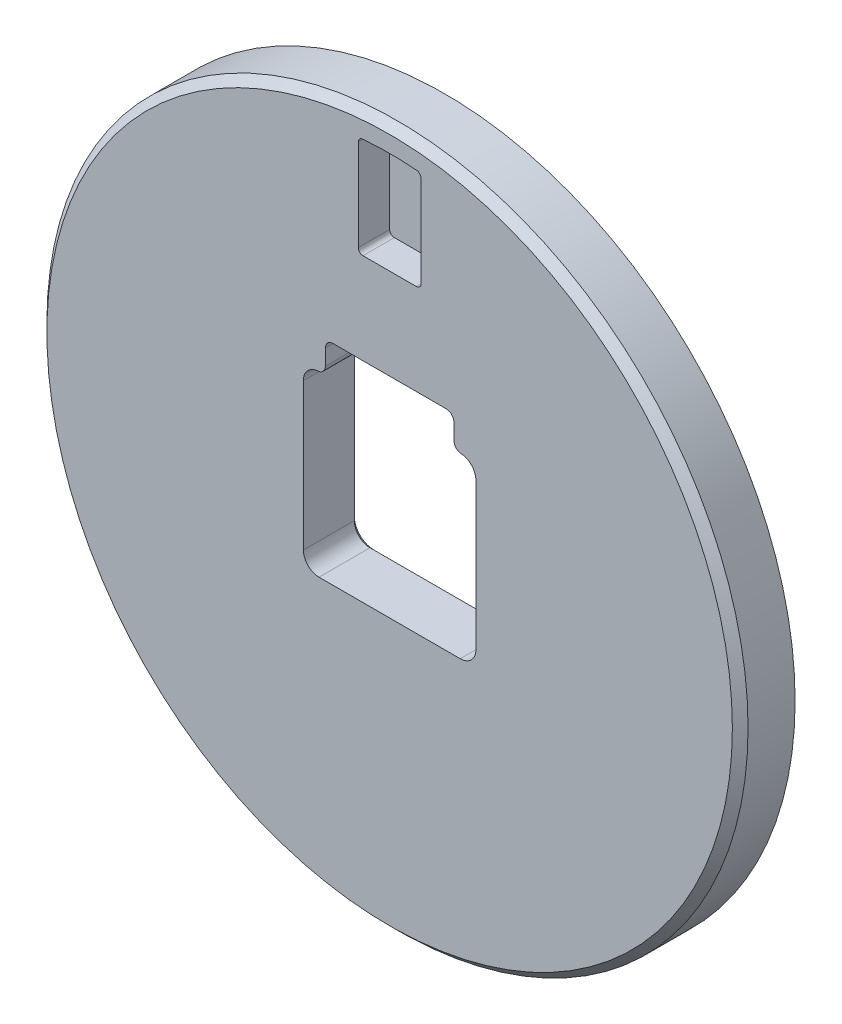
SolidWorks part; units mm, degrees
ref_plane "前视基准面" through (0, 0, 0) normal (0, 0, 1) x (1, 0, 0)
ref_plane "上视基准面" through (0, 0, 0) normal (0, 1, 0) x (1, 0, 0)
ref_plane "右视基准面" through (0, 0, 0) normal (1, 0, 0) x (0, 0, -1)
sketch "草图1" plane through (0, 0, 0) normal (0, 0, 1) x (1, 0, 0)
  circle A0 centre (0, 0) radius 22.35
extrude "凸台-拉伸1" add sketch "草图1" along normal blind 3.5
sketch "草图2" plane through (0, 0, 0) normal (0, 0, 1) x (1, 0, 0)
  line L1 (-5.5, 0) -> (-5.5, 5.5)
  line L2 (-4.5, 6.5) -> (4.5, 6.5)
  line L4 (-4.5, -4.85) -> (4.5, -4.85)
  line L5 (-5.5, -3.85) -> (-5.5, 0)
  line L6 (5.5, 5.5) -> (5.5, -3.85)
  arc A0 (-5.5, -3.85) -> (-4.5, -4.85) centre (-4.5, -3.85) ccw
  arc A1 (5.5, -3.85) -> (4.5, -4.85) centre (4.5, -3.85) cw
  arc A2 (4.5, 6.5) -> (5.5, 5.5) centre (4.5, 5.5) cw
  arc A3 (-5.5, 5.5) -> (-4.5, 6.5) centre (-4.5, 5.5) cw
  dimension "D1" = 1
extrude "切除-拉伸1" cut sketch "草图2" against normal up to surface (3.5 mm away) from surface at 3.5 up to face at (22.35, 0, 0) starting at face at (22.35, 0, 3.5)
chamfer "倒角1" distance 0.5 angle 45 1 edges at (22.35, 0, 3.5)
sketch "草图3" plane through (0, 0, 0) normal (0, 0, 1) x (1, 0, 0)
  line L0 (0, 6.5) -> (-4.1, 6.5)
  line L1 (-4.5, 6.5) -> (4.5, 6.5) construction
  line L2 (0, 6.5) -> (4.1, 6.5)
  line L3 (-4.1, 6.5) -> (-4.1, 8.5)
  line L4 (-4.1, 8.5) -> (4.1, 8.5)
  line L5 (4.1, 8.5) -> (4.1, 6.5)
extrude "切除-拉伸2" cut sketch "草图3" against normal up to surface (3.5 mm away) from surface at 3.5 up to face at (22.35, 0, 0) starting at face at (21.85, 0, 3.5)
fillet "圆角1" radius 0.5 4 edges at (4.1, 6.5, 1.75) (-4.1, 6.5, 1.75) (4.1, 8.5, 1.75) (-4.1, 8.5, 1.75)
chamfer "倒角2" distance 0.25 angle 45 14 edges at (-4.2349, 6.6551, 0) (-5.2303, 6.1831, 0) (-4.1, 7.4983, 0) (-5.5, 0.825, 0) (-3.9536, 8.3536, 0) (-5.2071, -4.5571, 0) (0, 8.5, 0) (0, -4.85, 0) (3.9536, 8.3536, 0) (5.2071, -4.5571, 0) (4.1, 7.4983, 0) (4.2349, 6.6551, 0) (5.2303, 6.1831, 0) (5.5, 0.825, 0)
sketch "草图4" plane through (0, 0, 0) normal (0, 0, 1) x (1, 0, 0)
  line L0 (-2, 20.7) -> (-2, 19.7)
  line L2 (0, 14.3) -> (-2, 14.3)
  line L3 (0, 14.3) -> (2, 14.3)
  line L4 (-2, 14.3) -> (-2, 19.7)
  line L5 (2, 14.3) -> (2, 19.7)
  line L6 (2, 19.7) -> (2, 20.7)
  arc A0 (-2, 20.7) -> (2, 20.7) centre (0, 1) cw
extrude "切除-拉伸3" cut sketch "草图4" against normal blind 2 from surface at 3.5 starting at face at (21.85, 0, 3.5)
fillet "圆角2" radius 0.3 4 edges at (-2, 14.3, 2.5) (2, 14.3, 2.5) (2, 20.7, 2.5) (-2, 20.7, 2.5)
